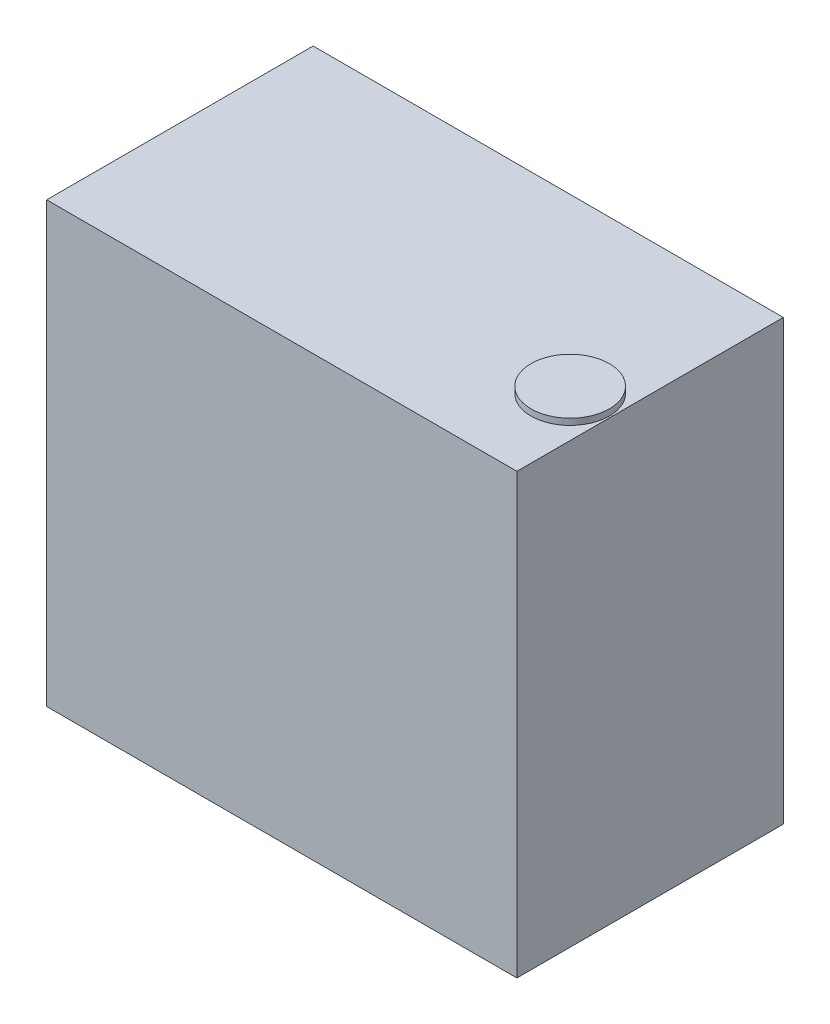
SolidWorks part; units mm, degrees
ref_plane "Piano frontale" through (0, 0, 0) normal (0, 0, 1) x (1, 0, 0)
ref_plane "Piano superiore" through (0, 0, 0) normal (0, 1, 0) x (1, 0, 0)
ref_plane "Piano destro" through (0, 0, 0) normal (1, 0, 0) x (0, 0, -1)
sketch "Schizzo1" plane through (0, 0, 0) normal (0, 0, 1) x (1, 0, 0)
  line L1 (0, 0) -> (150, 0)
  line L2 (0, 0) -> (0, 140)
  line L3 (0, 140) -> (150, 140)
  line L4 (150, 0) -> (150, 140)
  dimension "D1" = 150
  dimension "D2" = 140
extrude "Estrusione-Estrusione1" add sketch "Schizzo1" along normal blind 85
sketch "Schizzo2" plane through (0, 0, 0) normal (0, -1, 0) x (1, 0, 0)
  line L0 (104, 13) -> (94, 24)
  line L1 (110, 55) -> (130, 55)
  line L2 (110, 55) -> (110, 70)
  line L3 (110, 70) -> (130, 70)
  line L4 (130, 55) -> (130, 70)
  line L5 (104, 35) -> (134, 35)
  line L6 (104, 35) -> (104, 13)
  line L7 (104, 13) -> (134, 13)
  line L8 (134, 35) -> (134, 13)
  line L9 (94, 24) -> (104, 35)
  line L10 (134, 35) -> (144, 24)
  line L11 (144, 24) -> (134, 13)
  line L12 (94, 24) -> (104, 24)
  line L13 (104, 24) -> (134, 24)
  line L14 (134, 24) -> (144, 24)
  line L15 (150, 85) -> (150, 0) construction
  line L16 (0, 85) -> (150, 85) construction
  line L17 (0, 0) -> (150, 0) construction
  dimension "D1" = 50
  dimension "D2" = 22
  dimension "D3" = 30
  dimension "D4" = 15
  dimension "D5" = 20
  dimension "D6" = 20
  dimension "D7" = 15
  dimension "D8" = 16
  dimension "D9" = 13
extrude "Estrusione-Estrusione2" add sketch "Schizzo2" along normal blind 4 contours L1 L4 L3 L2 | L9 L12 L6 | L12 L0 L6 | L6 L13 L8 L5 | L13 L6 L7 L8 | L8 L14 L10 | L14 L8 L11
sketch "Schizzo3" plane through (0, 0, 0) normal (0, -1, 0) x (1, 0, 0)
  line L0 (0, 85) -> (0, 0) construction
  line L1 (0, 85) -> (150, 85) construction
  line L2 (0, 0) -> (150, 0) construction
  line L3 (150, 85) -> (150, 0) construction
  circle A0 centre (5, 80) radius 1.5
  circle A1 centre (5, 15) radius 1.5
  circle A2 centre (120, 6) radius 1.5
  circle A3 centre (143, 80) radius 1.5
  dimension "D1" = 3
  dimension "D2" = 3
  dimension "D3" = 3
  dimension "D4" = 3
  dimension "D5" = 5
  dimension "D6" = 5
  dimension "D7" = 5
  dimension "D8" = 15
  dimension "D9" = 6
  dimension "D11" = 7
  dimension "D12" = 5
  dimension "D10" = 30
extrude "Taglio-Estrusione1" cut sketch "Schizzo3" against normal blind 10
sketch "Schizzo4" plane through (0, 140, 0) normal (0, 1, 0) x (1, 0, 0)
  line L0 (150, 0) -> (0, 0) construction
  line L1 (150, -85) -> (150, 0) construction
  circle A0 centre (137, -55) radius 12.5
  dimension "D1" = 25
  dimension "D2" = 55
  dimension "D3" = 13
extrude "Estrusione-Estrusione3" add sketch "Schizzo4" along normal blind 2
